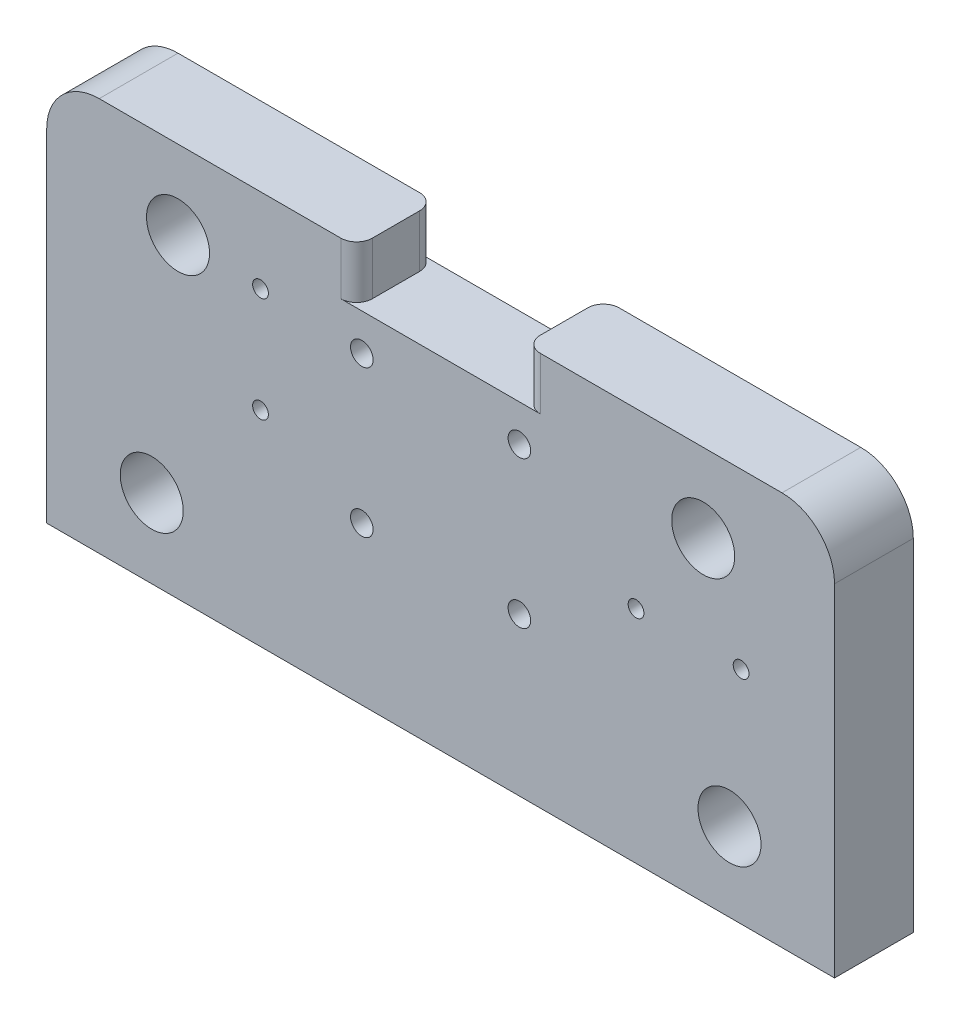
SolidWorks part; units mm, degrees
material "三聚氰胺甲醛树脂"
ref_plane "前视基准面" through (0, 0, 0) normal (0, 0, 1) x (1, 0, 0)
ref_plane "上视基准面" through (0, 0, 0) normal (0, 1, 0) x (1, 0, 0)
ref_plane "右视基准面" through (0, 0, 0) normal (1, 0, 0) x (0, 0, -1)
sketch "草图1" plane through (0, 0, 0) normal (0, 0, 1) x (1, 0, 0)
  line L0 (16, 37.5) -> (65, 37.5)
  line L1 (-65, 37.5) -> (-16, 37.5)
  line L2 (-75, 27.5) -> (-75, -37.5)
  line L3 (-75, -37.5) -> (75, -37.5)
  line L4 (75, 27.5) -> (75, -37.5)
  line L5 (-75, 37.5) -> (75, -37.5) construction
  line L6 (-75, -37.5) -> (75, 37.5) construction
  line L8 (-16, 37.5) -> (-16, 27.5)
  line L9 (-16, 27.5) -> (16, 27.5)
  line L10 (16, 37.5) -> (16, 27.5)
  arc A0 (-75, 27.5) -> (-65, 37.5) centre (-65, 27.5) cw
  arc A1 (75, 27.5) -> (65, 37.5) centre (65, 27.5) ccw
  circle A2 centre (-15, 20.5) radius 2.15
  circle A3 centre (15, 20.5) radius 2.15
  circle A4 centre (-15, -7.5) radius 2.15
  circle A5 centre (15, -7.5) radius 2.15
  point P0 (0, 0)
  point P20 (0, 27.5)
  dimension "D6" = 10
  dimension "D7" = 10
  dimension "D8" = 4.3
  dimension "D9" = 4.3
  dimension "D11" = 15
  dimension "D13" = 0
  dimension "D14" = 28
  dimension "D18" = 4.3
  dimension "D19" = 4.3
  dimension "D1" = 75
  dimension "D2" = 150
  dimension "D3" = 10
  dimension "D4" = 32
  dimension "D5" = 59
  dimension "D10" = 30
  dimension "D12" = 7
  dimension "D15" = 28
  dimension "D16" = 30
  dimension "D17" = 0
extrude "凸台-拉伸1" add sketch "草图1" along normal blind 15 contours A2 | A3 | L1 L8 L9 L10 L0 A1 L4 L3 L2 A0 | A5 | A4
sketch "草图2" plane through (0, 0, 15) normal (0, 0, 1) x (1, 0, 0)
  line L0 (-16, 27.5) -> (16, 27.5) construction
  line L1 (-75, -37.5) -> (75, -37.5) construction
  line L2 (-65, 37.5) -> (-16, 37.5) construction
  circle A0 centre (-50, 22.5) radius 6
  circle A1 centre (50, 22.5) radius 6
  circle A2 centre (-55, -22.5) radius 6
  circle A3 centre (55, -22.5) radius 6
  point P10 (0, 27.5)
  dimension "D1" = 12
  dimension "D2" = 12
  dimension "D3" = 12
  dimension "D4" = 12
  dimension "D6" = 0
  dimension "D7" = 100
  dimension "D9" = 50
  dimension "D11" = 15
  dimension "D12" = 15
  dimension "D5" = 110
  dimension "D8" = 55
  dimension "D10" = 0
extrude "切除-拉伸1" cut sketch "草图2" against normal through all
fillet "圆角1" radius 3 4 edges at (16, 32.5, 0) (16, 32.5, 15) (-16, 32.5, 0) (-16, 32.5, 15)
sketch "草图3" plane through (0, 0, 15) normal (0, 0, 1) x (1, 0, 0)
  line L0 (-65, 37.5) -> (-19, 37.5) construction
  line L1 (-75, 27.5) -> (-75, -37.5) construction
  circle A0 centre (-34.29, 1.5) radius 1.5
  circle A1 centre (-34.29, 21.5) radius 1.5
  dimension "D1" = 0
  dimension "D2" = 20
  dimension "D3" = 36
  dimension "D4" = 40.71
  dimension "D5" = 3
  dimension "D6" = 3
extrude "切除-拉伸2" cut sketch "草图3" against normal through all
sketch "草图4" plane through (0, 0, 15) normal (0, 0, 1) x (1, 0, 0)
  line L0 (75, 27.5) -> (75, -37.5) construction
  line L1 (19, 37.5) -> (65, 37.5) construction
  circle A0 centre (57.21, 4.5) radius 1.5
  circle A1 centre (37.21, 4.5) radius 1.5
  dimension "D1" = 17.79
  dimension "D2" = 33
  dimension "D3" = 3
  dimension "D4" = 3
  dimension "D5" = 0
  dimension "D6" = 20
extrude "切除-拉伸3" cut sketch "草图4" against normal through all contours A1 | A0
